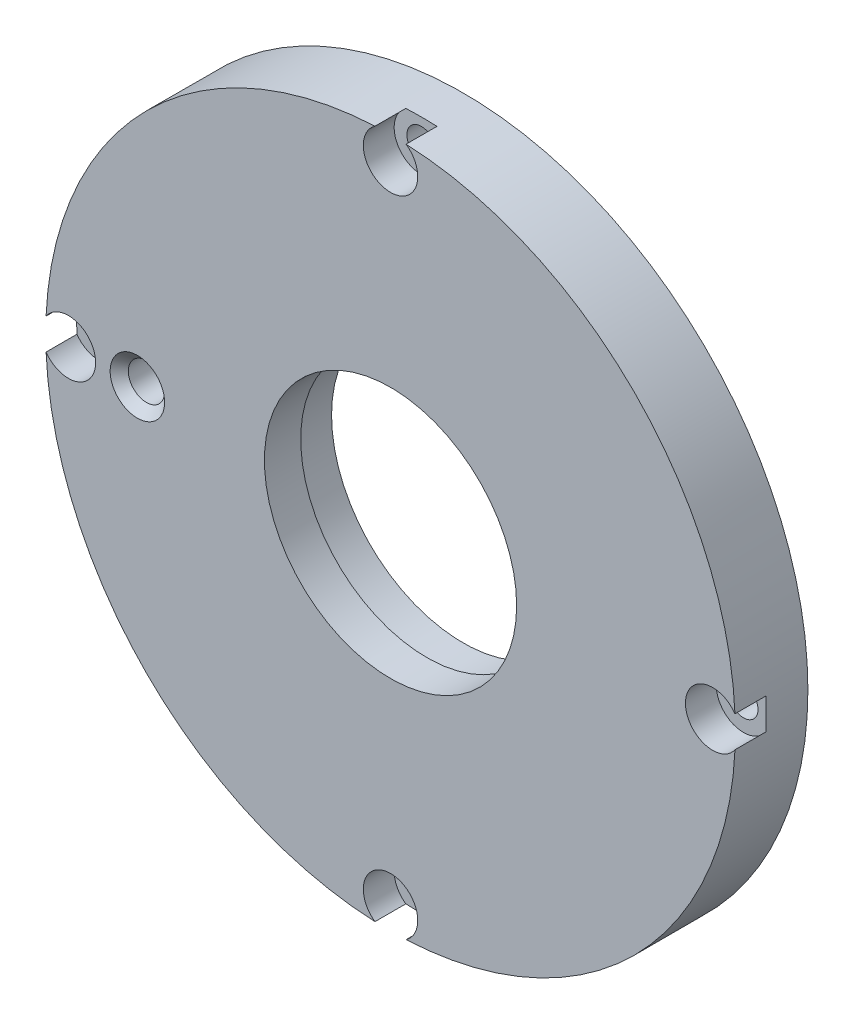
SolidWorks part; units mm, degrees
material "6061 合金"
ref_plane "前视基准面" through (0, 0, 0) normal (0, 0, 1) x (1, 0, 0)
ref_plane "上视基准面" through (0, 0, 0) normal (0, 1, 0) x (1, 0, 0)
ref_plane "右视基准面" through (0, 0, 0) normal (1, 0, 0) x (0, 0, -1)
sketch "草图1" plane through (0, 0, 0) normal (0, 0, 1) x (1, 0, 0)
  circle A0 centre (0, 0) radius 38
  circle A1 centre (0, 0) radius 13.9
  dimension "D1" = 76
  dimension "D2" = 27.8
extrude "凸台-拉伸1" add sketch "草图1" along normal blind 8
hole_wizard "打孔尺寸(%根据)内六角圆柱头螺钉的类型1" positions "草图4" profile "草图5" counterbore size "M3" standard "GB" end condition up to next
sketch "草图4" plane through (0, 0, 8) normal (0, 0, 1) x (1, 0, 0)
  circle A0 centre (0, 0) radius 35.5 construction
  point P0 (0, 35.5)
  point P16 (35.5, 0)
  point P17 (0, -35.5)
  point P18 (-35.5, 0)
  dimension "D1" = 71
  dimension "D2" = 4
sketch "草图5" plane through (0, 35.5, 8) normal (1, 0, 0) x (0, -1, 0)
  line L0 (0, 0) -> (0, 8)
  line L1 (0, 8) -> (1.6, 8)
  line L3 (1.6, 8) -> (1.6, 3.4)
  line L4 (1.6, 3.4) -> (3, 3.4)
  line L5 (3, 3.4) -> (3, 0)
  line L7 (3, 0) -> (0, 0)
  line L11 (0, -6.35) -> (0, 107.95) construction
  dimension "通孔孔直径" = 3.2
  dimension "通孔孔深度" = 8
  dimension "柱形沉头孔直径" = 6
  dimension "柱形沉头孔深度" = 3.4
hole_wizard "Ø4.0 (4) 直径孔1" positions "草图8" profile "草图7" hole size "Ø4.0" standard "GB" end condition up to next
sketch "草图8" plane through (0, 0, 0) normal (0, 0, -1) x (-1, 0, 0)
  line L0 (0, 0) -> (30.5332, 0) construction
  line L2 (0, 0) -> (0, -10.3474) construction
  circle A1 centre (0, 0) radius 13.9 construction
  point P0 (27.9, 0)
  dimension "D1" = 14
  dimension "D2" = 90
sketch "草图7" plane through (-27.9, 0, 0) normal (1, 0, 0) x (0, 1, 0)
  line L0 (0, 0) -> (0, 8)
  line L1 (0, 8) -> (2, 8)
  line L2 (2, 8) -> (2, 0)
  line L5 (2, 0) -> (0, 0)
  line L11 (0, -6.35) -> (0, 107.95) construction
  dimension "通孔孔直径" = 4
  dimension "通孔孔深度" = 8
chamfer "倒角1" distance 1 angle 45 2 edges at (-29.9, 0, 0) (-25.9, 0, 8)
sketch "草图9" plane through (0, 0, 0) normal (0, 0, 1) x (1, 0, 0)
  circle A0 centre (0, 0) radius 14.5
  dimension "D1" = 29
extrude "切除-拉伸1" cut sketch "草图9" along normal offset from surface (4 mm away) 4 up to face at (-24.9, 0, 8)
